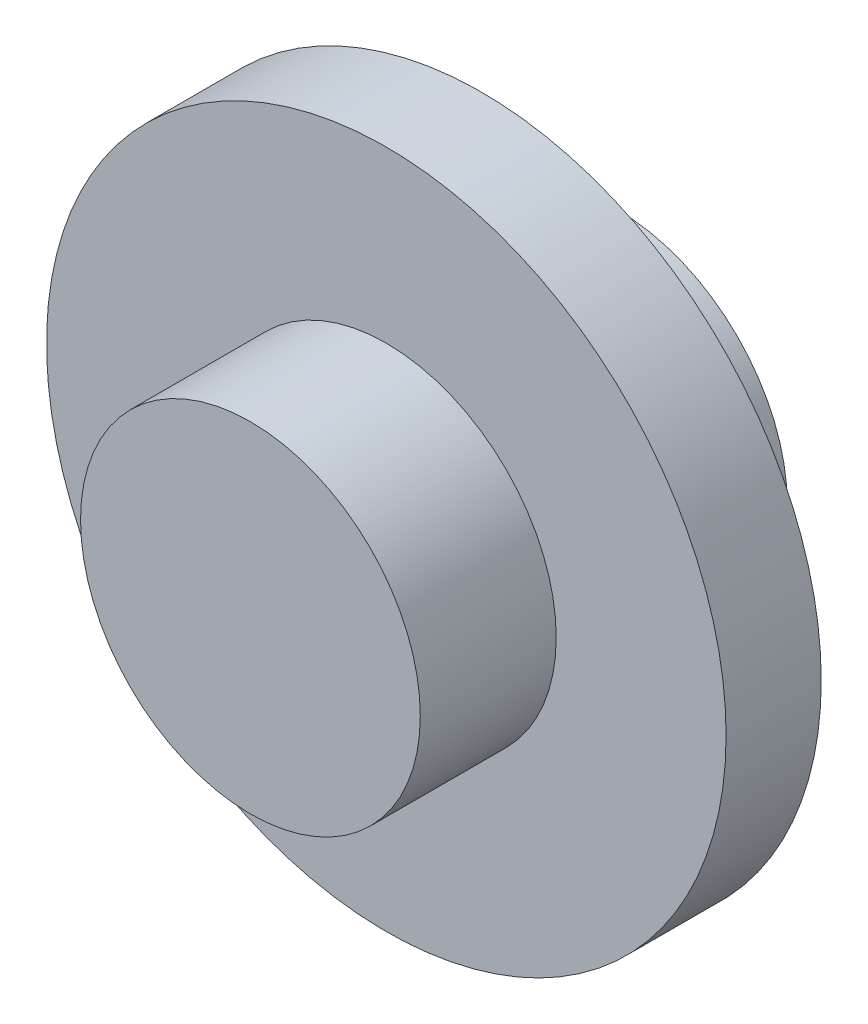
SolidWorks part; units mm, degrees
ref_plane "前视基准面" through (0, 0, 0) normal (0, 0, 1) x (1, 0, 0)
ref_plane "上视基准面" through (0, 0, 0) normal (0, 1, 0) x (1, 0, 0)
ref_plane "右视基准面" through (0, 0, 0) normal (1, 0, 0) x (0, 0, -1)
sketch "草图1" plane through (0, 0, 0) normal (0, 0, 1) x (1, 0, 0)
  circle A0 centre (0, 0) radius 12.5
  dimension "D1" = 25
extrude "凸台-拉伸1" add sketch "草图1" along normal blind 10
sketch "草图2" plane through (0, 0, 10) normal (0, 0, 1) x (1, 0, 0)
  circle A0 centre (0, 0) radius 25
  dimension "D1" = 50
extrude "凸台-拉伸2" add sketch "草图2" along normal blind 7
sketch "草图3" plane through (0, 0, 17) normal (0, 0, 1) x (1, 0, 0)
  circle A0 centre (0, 0) radius 12.5
  dimension "D1" = 25
extrude "凸台-拉伸3" add sketch "草图3" along normal blind 10
